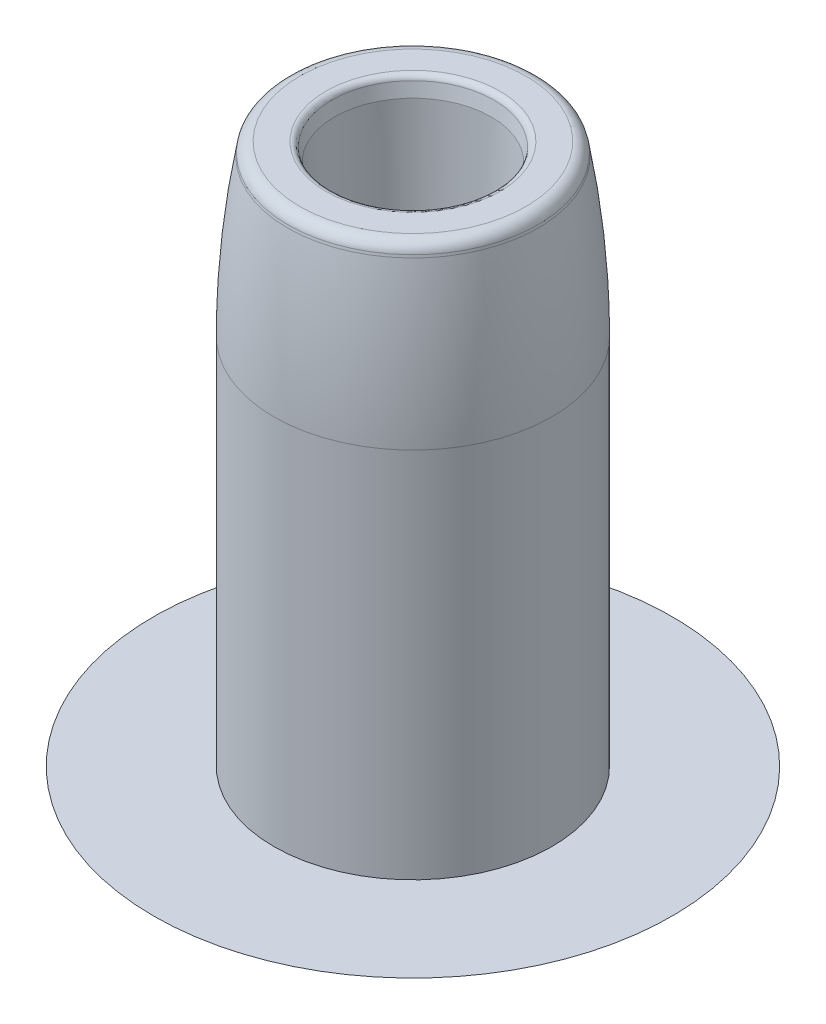
SolidWorks part; units mm, degrees
ref_plane "Front Plane" through (0, 0, 0) normal (0, 0, 1) x (1, 0, 0)
ref_plane "Top Plane" through (0, 0, 0) normal (0, 1, 0) x (1, 0, 0)
ref_plane "Right Plane" through (0, 0, 0) normal (1, 0, 0) x (0, 0, -1)
sketch "Sketch2" plane through (0, 0, 0) normal (1, 0, 0) x (0, 0, -1)
  line L0 (1.8415, 25.2095) -> (-1.8415, -25.2095) construction
  line L1 (-1.8415, 25.2095) -> (1.8415, 25.2095) construction
  line L2 (-1.8415, 25.2095) -> (-1.8415, -25.2095) construction
  line L3 (-1.8415, -25.2095) -> (1.8415, -25.2095) construction
  line L4 (1.8415, 25.2095) -> (1.8415, -25.2095) construction
  dimension "D1" = 3.683
  dimension "D2" = 50.419
sketch "Sketch3" plane through (0, 0, 0) normal (1, 0, 0) x (0, 0, -1)
  line L0 (-3.3314, 0.1905) -> (-2.9504, -13.7795)
  line L1 (-2.9504, -13.7795) -> (-2.9504, -22.6695)
  line L2 (-2.9504, -22.6695) -> (0, -22.6695)
  line L3 (0, -22.6695) -> (0, -25.2095) construction
  line L6 (-5.8714, 0.1905) -> (-3.3314, 0.1905)
  line L7 (0, -25.2095) -> (-10.9514, -25.2095) construction
  line L8 (-10.9514, -25.2095) -> (-10.9514, -22.6695) construction
  line L9 (-10.9514, -22.6695) -> (-5.8714, -22.6695)
  line L10 (-5.8714, -22.6695) -> (-5.8714, 0.1905)
  line L12 (-1.8415, -25.2095) -> (1.8415, -25.2095) construction
  line L15 (-3.3314, 0.1905) -> (-2.9504, 0.1905) construction
  line L16 (-2.9504, 0.1905) -> (-2.9504, -13.7795) construction
  line L17 (0, -24.1935) -> (7.4517, -24.1935) construction
  line L18 (0, -22.6695) -> (0, -24.1935)
  spline S0 degree 3 poles (-10.9514, -22.6695) (-7.6736, -23.8786) (-8.4247, -25.0577) (-3.7609, -24.0397) (-1.0962, -24.1935) (0, -24.1935) knots 0 0 0 0 0.34523 0.440288 1 1 1 1
  point P14 (-2.9504, -15.1086)
  dimension "D7" = 1.524
  dimension "D1" = 2.54
  dimension "D2" = 5.08
  dimension "D3" = 22.86
  dimension "D4" = 2.54
  dimension "D5" = 0.381
  dimension "D6" = 8.89
revolve "Revolve1" add sketch "Sketch3" angle 360 about L3
chamfer "Chamfer1" distance 3.81 angle 10 1 edges at (0, 0.1905, 5.8714)
fillet "Fillet2" radius 0.508 1 edges at (0, 0.1905, 5.1996)
fillet "Fillet3" radius 38.1 1 edges at (0, -3.6195, 5.8714)
chamfer "Chamfer2" distance 0.762 angle 10 1 edges at (0, 0.1905, 3.3314)
fillet "Fillet4" radius 0.254 1 edges at (0, 0.1905, 3.4665)
sketch "Sketch5" plane through (0.2218, -18.5798, 0) normal (1, 0.0048, 0) x (0, 0, -1)
  line L0 (-1.7998, -4.0892) -> (-1.7998, 46.3298) construction
  line L1 (-66.4644, -4.0892) -> (62.8649, -4.0892)
  line L2 (-66.4644, -4.0892) -> (-66.4644, 46.3298)
  line L3 (-66.4644, 46.3298) -> (62.8649, 46.3298)
  line L4 (62.8649, -4.0892) -> (62.8649, 46.3298)
  dimension "D1" = 50.419
sketch "Sketch6" plane through (0, -22.6695, 0) normal (0, 1, 0) x (1, 0, 0)
  circle A1 centre (0, 0) radius 2.9504
  circle A2 centre (0, 0) radius 2.9504
  dimension "D1" = 0
extrude "Cut-Extrude1" cut sketch "Sketch6" against normal through all
fillet "Fillet5" radius 2.54 1 edges at (0, -24.2045, 2.9504)
